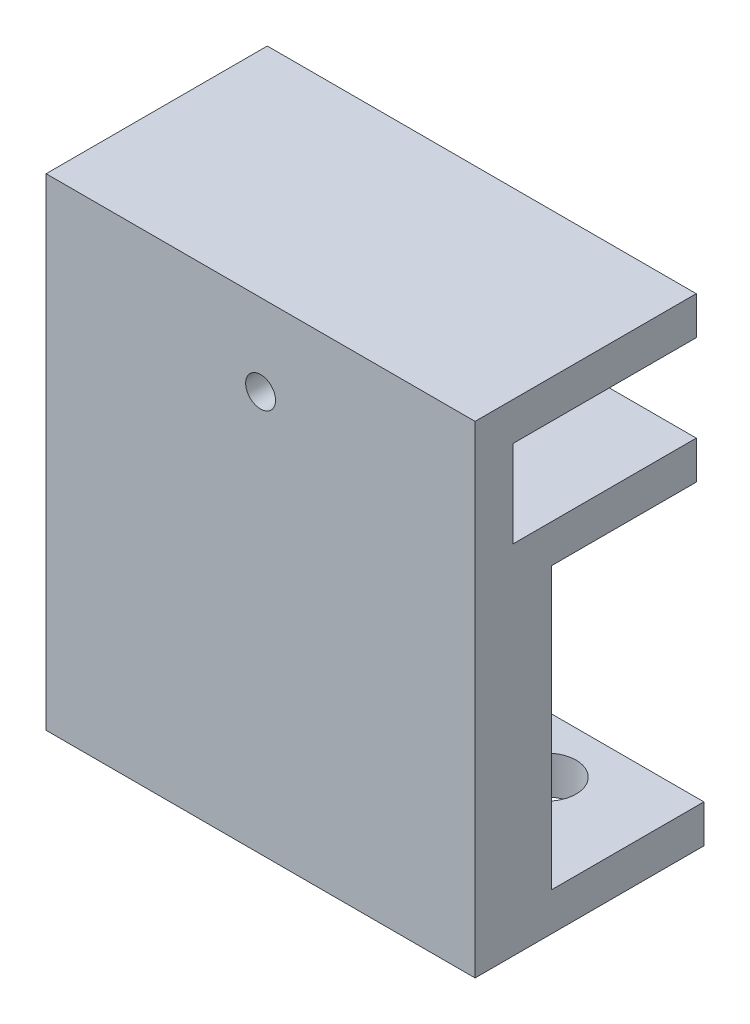
SolidWorks part; units mm, degrees
ref_plane "Front Plane" through (0, 0, 0) normal (0, 0, 1) x (1, 0, 0)
ref_plane "Top Plane" through (0, 0, 0) normal (0, 1, 0) x (1, 0, 0)
ref_plane "Right Plane" through (0, 0, 0) normal (1, 0, 0) x (0, 0, -1)
sketch "Sketch1" plane through (0, 0, 0) normal (1, 0, 0) x (0, 0, -1)
  line L0 (24.13, 27.178) -> (-12.7, 27.178)
  line L2 (-12.7, -53.086) -> (25.4, -53.086)
  line L3 (25.4, -53.086) -> (25.4, -46.736)
  line L4 (25.4, -46.736) -> (0, -46.736)
  line L5 (0, 55) -> (0, -55) construction
  line L6 (0, -46.736) -> (0, 0)
  line L7 (0, 0) -> (24.13, 0)
  line L8 (24.13, 0) -> (24.13, 6.35)
  line L9 (24.13, 6.35) -> (-6.35, 6.35)
  line L10 (-6.35, 6.35) -> (-6.35, 20.828)
  line L11 (-6.35, 20.828) -> (24.13, 20.828)
  line L12 (24.13, 20.828) -> (24.13, 27.178)
  line L13 (55, 0) -> (-55, 0) construction
  line L15 (-12.7, 0) -> (-12.7, 27.178)
  line L17 (-12.7, 0) -> (-12.7, -53.086)
  point P16 (0, 0)
  point P17 (0, 0)
  point P20 (0, 0)
  dimension "D1" = 14.478
  dimension "D2" = 6.35
  dimension "D3" = 25.4
  dimension "D4" = 6.35
  dimension "D5" = 6.35
  dimension "D6" = 6.35
  dimension "D7" = 53.086
  dimension "D8" = 36.83
  dimension "D9" = 12.7
extrude "Boss-Extrude1" add sketch "Sketch1" along normal mid plane 71.4248
sketch "Sketch2" plane through (0, 0, 12.7) normal (0, 0, 1) x (1, 0, 0)
  line L0 (35.7124, 27.178) -> (-35.7124, 27.178) construction
  line L1 (0, -20.955) -> (0, 20.955) construction
  point P0 (0, 13.589)
  point P3 (0, 0)
  dimension "D1" = 13.589
hole_wizard "#10 Clearance Hole1" positions "Sketch3" profile "Sketch4" hole size "#10" standard "ANSI Inch" end condition through all
sketch "Sketch3" plane through (0, 0, 12.7) normal (0, 0, 1) x (1, 0, 0)
  point P0 (0, 13.589)
sketch "Sketch4" plane through (0, 13.589, 12.7) normal (1, 0, 0) x (0, -1, 0)
  line L0 (0, 0) -> (0, 38.1)
  line L1 (0, 38.1) -> (2.4892, 38.1)
  line L2 (2.4892, 38.1) -> (2.4892, 0)
  line L5 (2.4892, 0) -> (0, 0)
  line L11 (0, -6.35) -> (0, 107.95) construction
  dimension "Thru Hole Dia." = 4.9784
  dimension "Thru Hole Depth" = 38.1
sketch "Sketch5" plane through (0, -53.086, 0) normal (0, -1, 0) x (1, 0, 0)
  line L0 (-35.7124, 12.7) -> (-35.7124, -25.4) construction
  line L1 (19.05, -15.875) -> (-19.05, -15.875) construction
  line L2 (0, -20.955) -> (0, 20.955) construction
  line L3 (35.7124, -25.4) -> (-35.7124, -25.4) construction
  point P0 (19.05, -15.875)
  point P1 (-19.05, -15.875)
  point P6 (0, -15.875)
  dimension "D1" = 16.6624
  dimension "D2" = 9.525
hole_wizard "3/8 Clearance Hole1" positions "Sketch6" profile "Sketch7" hole size "3/8" standard "ANSI Inch"
sketch "Sketch6" plane through (0, -53.086, 0) normal (0, -1, 0) x (-1, 0, 0)
  point P0 (-19.05, 15.875)
  point P3 (19.05, 15.875)
sketch "Sketch7" plane through (19.05, -53.086, -15.875) normal (1, 0, 0) x (0, 0, -1)
  line L0 (0, 0) -> (0, 6.35)
  line L1 (0, 6.35) -> (4.9022, 6.35)
  line L2 (4.9022, 6.35) -> (4.9022, 0)
  line L5 (4.9022, 0) -> (0, 0)
  line L11 (0, -6.35) -> (0, 107.95) construction
  dimension "Thru Hole Dia." = 9.8044
  dimension "Thru Hole Depth" = 6.35
